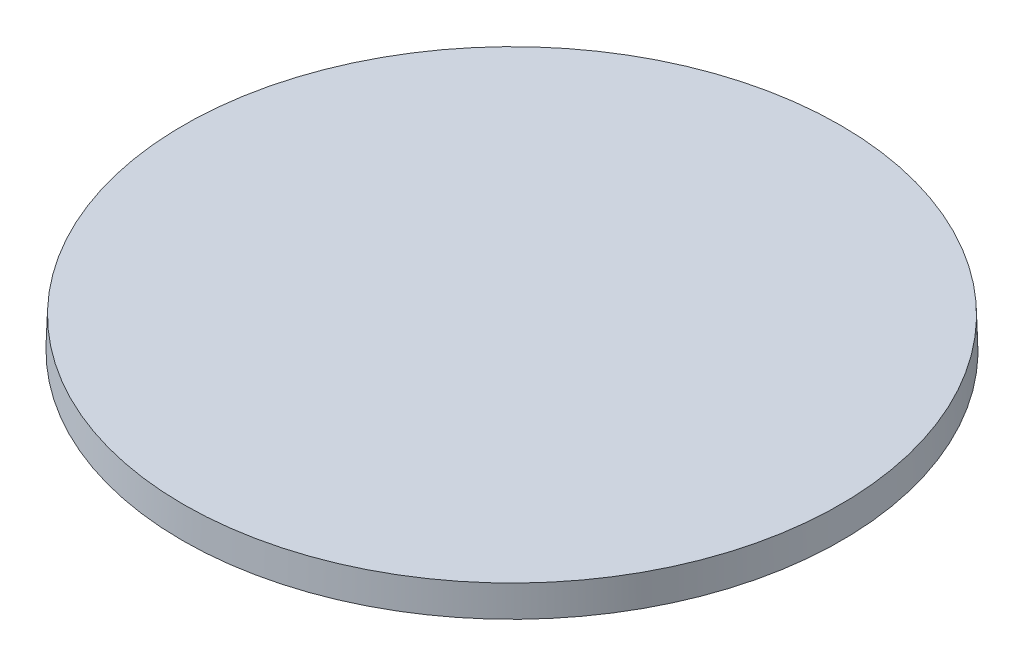
SolidWorks part; units mm, degrees
ref_plane "Front Plane" through (0, 0, 0) normal (0, 0, 1) x (1, 0, 0)
ref_plane "Top Plane" through (0, 0, 0) normal (0, 1, 0) x (1, 0, 0)
ref_plane "Right Plane" through (0, 0, 0) normal (1, 0, 0) x (0, 0, -1)
sketch "Sketch1" plane through (0, 0, 0) normal (0, 1, 0) x (1, 0, 0)
  circle A0 centre (0, 0) radius 16.12
  dimension "D1" = 32.24
extrude "Boss-Extrude1" add sketch "Sketch1" along normal blind 1.5 draft 2
